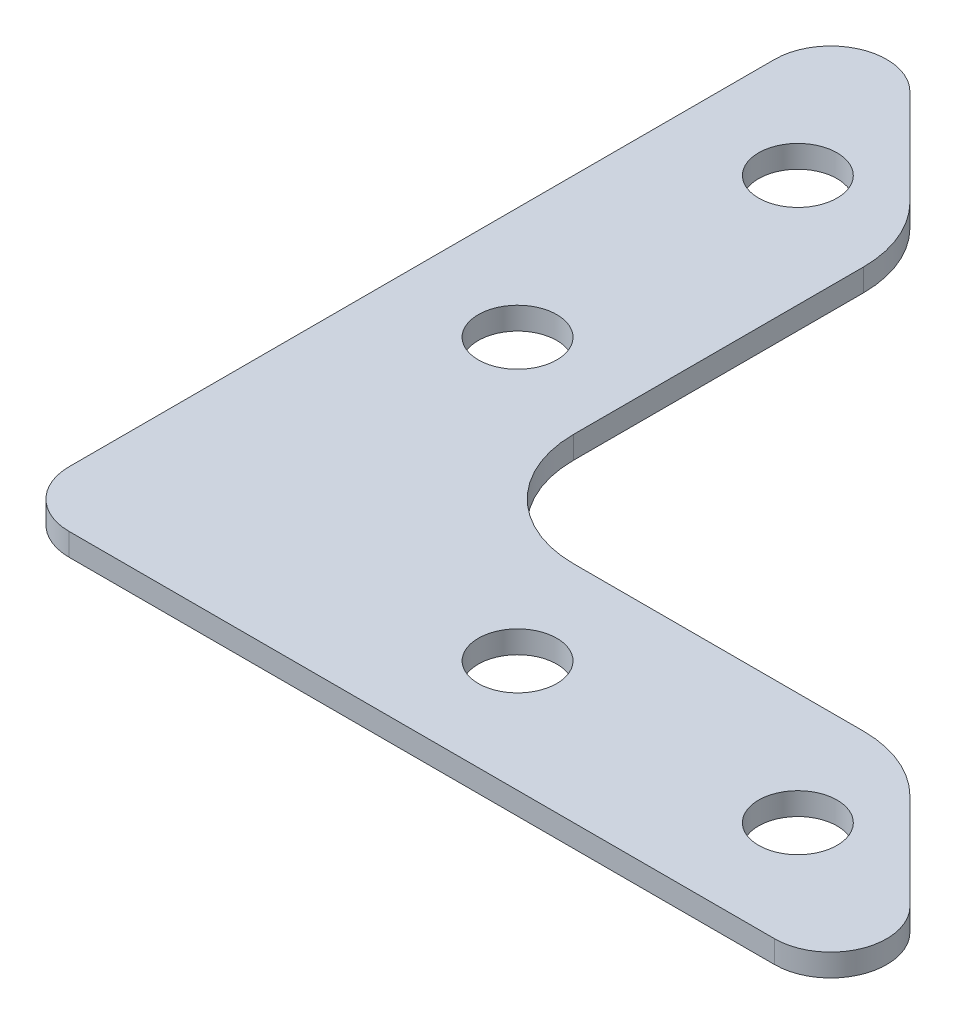
SolidWorks part; units mm, degrees
ref_plane "Front Plane" through (0, 0, 0) normal (0, 0, 1) x (1, 0, 0)
ref_plane "Top Plane" through (0, 0, 0) normal (0, 1, 0) x (1, 0, 0)
ref_plane "Right Plane" through (0, 0, 0) normal (1, 0, 0) x (0, 0, -1)
sketch "Sketch1" plane through (0, 0, 0) normal (0, 1, 0) x (1, 0, 0)
  line L0 (0, 5) -> (0, 67.9289)
  line L1 (71.4645, 8.5355) -> (62.9289, 17.0711)
  line L2 (67.9289, 0) -> (5, 0)
  line L3 (55.8579, 20) -> (30, 20)
  line L4 (20, 30) -> (20, 55.8579)
  line L5 (8.5355, 71.4645) -> (17.0711, 62.9289)
  arc A0 (0, 5) -> (5, 0) centre (5, 5) ccw
  arc A1 (67.9289, 0) -> (71.4645, 8.5355) centre (67.9289, 5) ccw
  arc A2 (8.5355, 71.4645) -> (0, 67.9289) centre (5, 67.9289) ccw
  circle A3 centre (10, 60) radius 3.5
  circle A4 centre (10, 35) radius 3.5
  circle A5 centre (35, 10) radius 3.5
  circle A6 centre (60, 10) radius 3.5
  arc A7 (20, 30) -> (30, 20) centre (30, 30) ccw
  arc A8 (17.0711, 62.9289) -> (20, 55.8579) centre (10, 55.8579) cw
  arc A9 (55.8579, 20) -> (62.9289, 17.0711) centre (55.8579, 10) cw
  point P6 (0, 0)
  point P9 (80, 0)
  point P12 (0, 80)
  point P23 (0, 0)
  point P27 (20, 20)
  point P30 (20, 60)
  dimension "D3" = 5
  dimension "D4" = 7
  dimension "D6" = 10
  dimension "D7" = 25
  dimension "D8" = 25
  dimension "D14" = 10
  dimension "D15" = 10
  dimension "D1" = 80
  dimension "D2" = 80
  dimension "D5" = 10
  dimension "D9" = 35
  dimension "D10" = 35
  dimension "D11" = 20
  dimension "D12" = 20
  dimension "D13" = 40
extrude "Boss-Extrude1" add sketch "Sketch1" along normal blind 2
